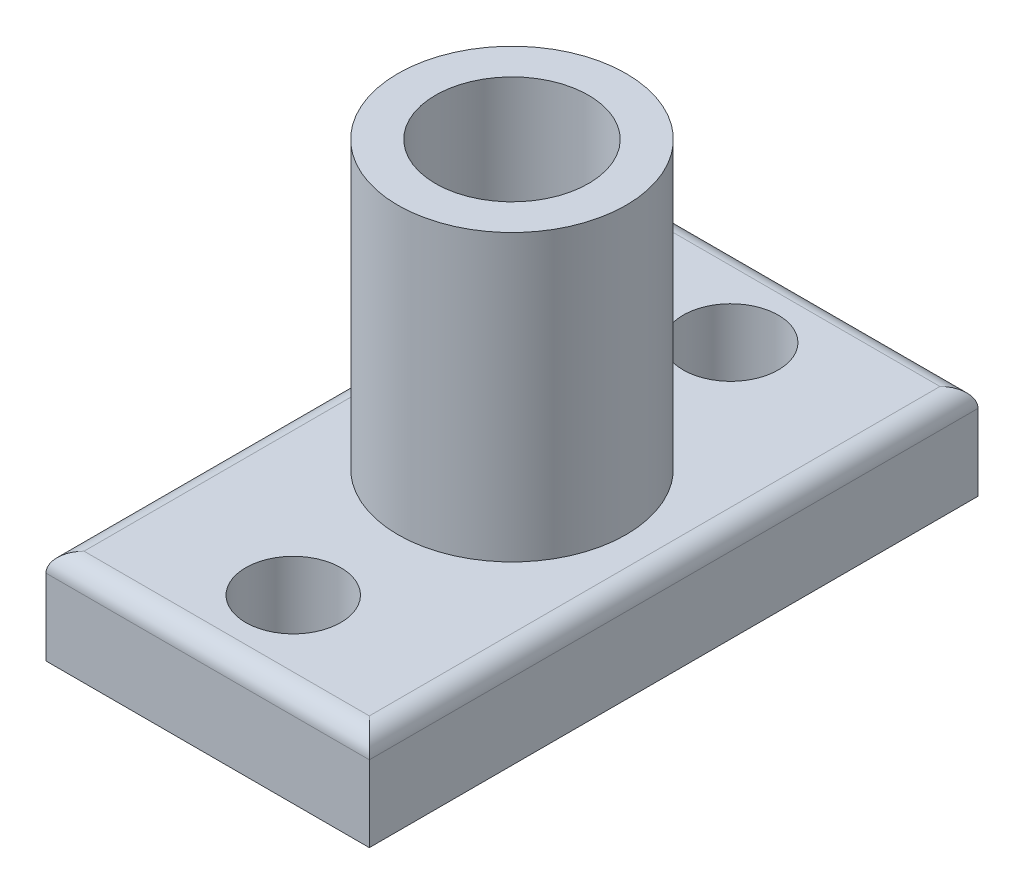
SolidWorks part; units mm, degrees
ref_plane "Front Plane" through (0, 0, 0) normal (0, 0, 1) x (1, 0, 0)
ref_plane "Top Plane" through (0, 0, 0) normal (0, 1, 0) x (1, 0, 0)
ref_plane "Right Plane" through (0, 0, 0) normal (1, 0, 0) x (0, 0, -1)
sketch "Sketch1" plane through (0, 0, 0) normal (0, 1, 0) x (1, 0, 0)
  line L1 (-8.5, -16) -> (8.5, -16)
  line L2 (-8.5, -16) -> (-8.5, 16)
  line L3 (-8.5, 16) -> (8.5, 16)
  line L4 (8.5, -16) -> (8.5, 16)
  line L5 (-8.5, -16) -> (8.5, 16) construction
  line L6 (-8.5, 16) -> (8.5, -16) construction
  circle A0 centre (0, 0) radius 6 construction
  circle A1 centre (0, 11.5) radius 2.5
  circle A2 centre (0, -11.5) radius 2.5
  point P0 (0, 0)
  dimension "D3" = 12
  dimension "D4" = 5
  dimension "D6" = 4.5
  dimension "D1" = 32
  dimension "D2" = 17
  dimension "D5" = 4.5
extrude "Boss-Extrude1" add sketch "Sketch1" along normal blind 5
sketch "Sketch2" plane through (0, 5, 0) normal (0, 1, 0) x (1, 0, 0)
  circle A0 centre (0, 0) radius 6
  circle A1 centre (0, 0) radius 4.025
  dimension "D1" = 8.05
  dimension "D2" = 12
extrude "Boss-Extrude2" add sketch "Sketch2" along normal blind 15
fillet "Fillet1" radius 1 4 edges at (0, 5, -16) (0, 5, 16) (-8.5, 5, 0) (8.5, 5, 0)
